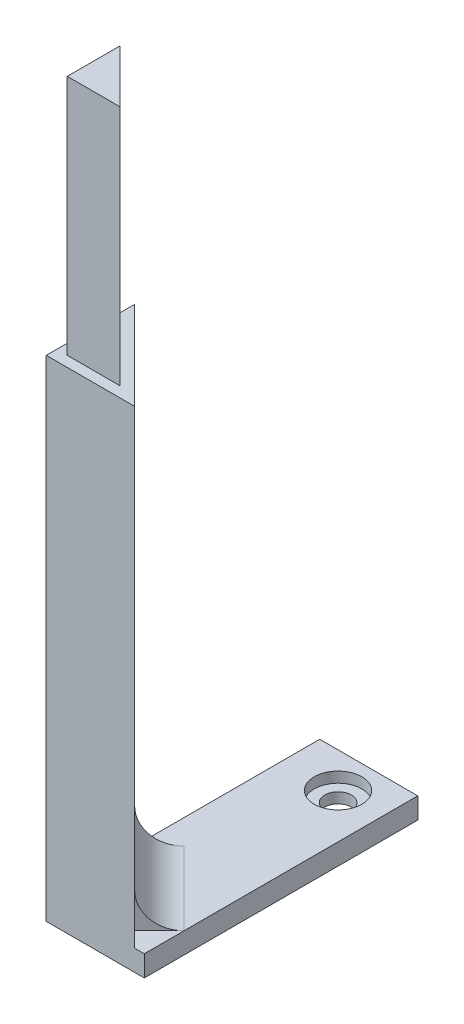
SolidWorks part; units mm, degrees
ref_plane "Front Plane" through (0, 0, 0) normal (0, 0, 1) x (1, 0, 0)
ref_plane "Top Plane" through (0, 0, 0) normal (0, 1, 0) x (1, 0, 0)
ref_plane "Right Plane" through (0, 0, 0) normal (1, 0, 0) x (0, 0, -1)
sketch "Sketch1" plane through (0, 0, 0) normal (0, 1, 0) x (1, 0, 0)
  line L9 (0, 0) -> (0, 15)
  line L35 (0, 0) -> (15, 0)
  line L50 (0, 15) -> (15, 0)
  point P0 (0, 0)
  point P5 (0, 0)
  point P6 (0, 0)
  point P9 (0, 0)
  point P10 (0, 0)
  dimension "D1" = 15
  dimension "D2" = 15
extrude "Boss-Extrude3" add sketch "Sketch1" along normal blind 320
sketch "Sketch7" plane through (0, 0, 0) normal (0, 0, 1) x (1, 0, 0)
  line L0 (15, 320) -> (0, 320)
  line L1 (0, 320) -> (0, 209)
  line L2 (0, 320) -> (0, 0) construction
  line L3 (0, 0) -> (15, 0) construction
  line L4 (15, 320) -> (15, 209)
  line L5 (15, 320) -> (15, 0) construction
  line L6 (15, 209) -> (0, 209)
  dimension "D1" = 209
extrude "Cut-Extrude3" cut sketch "Sketch7" against normal through all
sketch "Sketch10" plane through (0, 0, 0) normal (0, -1, 0) x (1, 0, 0)
  line L3 (-3, 3) -> (-3, -22.2426)
  line L4 (22.2426, 3) -> (-3, -22.2426)
  line L5 (-3, 3) -> (22.2426, 3)
extrude "Boss-Extrude7" add sketch "Sketch10" against normal blind 140
sketch "Sketch4" plane through (0, 0, 0) normal (0, -1, 0) x (1, 0, 0)
  line L5 (0, 0) -> (15, 0) construction
  line L9 (-3, 3) -> (25, 3)
  line L10 (25, 3) -> (25, -75.1)
  line L11 (-3, 3) -> (-3, -75.1)
  line L12 (-3, -75.1) -> (25, -75.1)
  circle A0 centre (12.3, -65.04) radius 3.8
  dimension "D3" = 7.6
  dimension "D5" = 65.04
  dimension "D1" = 78.1
  dimension "D2" = 28
extrude "Boss-Extrude4" add sketch "Sketch4" against normal blind 6
sketch "Sketch11" plane through (0, 6, 0) normal (0, 1, 0) x (1, 0, 0)
  line L0 (-3, 22.2426) -> (4.0711, 29.3137)
  line L1 (4.0711, 29.3137) -> (19.3157, 14.0691)
  line L2 (19.3157, 14.0691) -> (25, 8.3848)
  line L3 (25, -3) -> (25, 75.1) construction
  line L4 (25, 8.3848) -> (17.9289, 1.3137)
  line L5 (-3, 22.2426) -> (22.2426, -3) construction
  line L6 (17.9289, 1.3137) -> (-3, 22.2426)
  dimension "D1" = 10
extrude "Boss-Extrude8" add sketch "Sketch11" along normal blind 10
sketch "Sketch12" plane through (8.3076, 0, 8.3076) normal (0.7071, 0, 0.7071) x (0.7071, 0, -0.7071)
  line L0 (13.6066, 16) -> (23.6066, 16)
  line L1 (23.6066, 16) -> (23.6066, 6)
  arc A0 (13.6066, 16) -> (23.6066, 6) centre (23.6066, 16) ccw
extrude "Cut-Extrude4" cut sketch "Sketch12" against normal through all
sketch "Sketch13" plane through (0, 6, 0) normal (0, 1, 0) x (1, 0, 0)
  circle A0 centre (12.3, 65.04) radius 6.8
  circle A1 centre (12.3, 65.04) radius 3.8 construction
  dimension "D1" = 3
extrude "Cut-Extrude5" cut sketch "Sketch13" against normal blind 3
